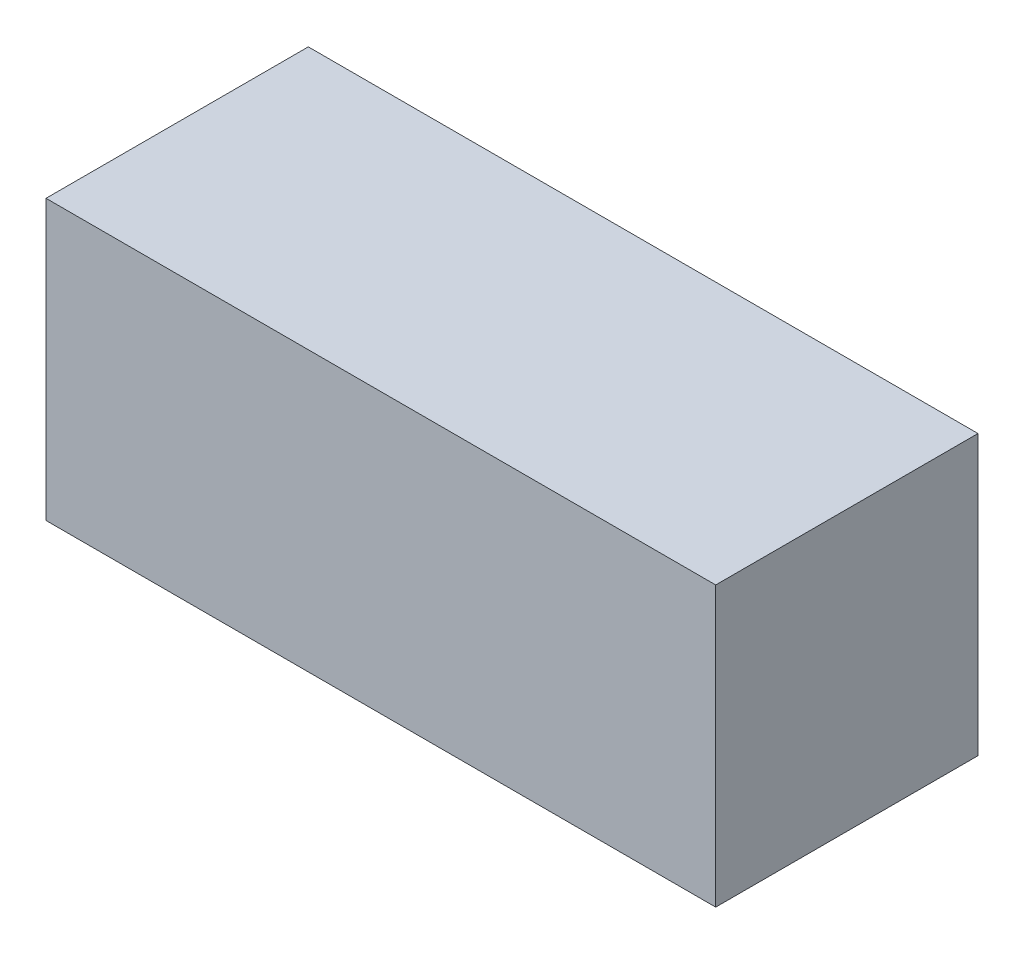
SolidWorks part; units mm, degrees
ref_plane "前视基准面" through (0, 0, 0) normal (0, 0, 1) x (1, 0, 0)
ref_plane "上视基准面" through (0, 0, 0) normal (0, 1, 0) x (1, 0, 0)
ref_plane "右视基准面" through (0, 0, 0) normal (1, 0, 0) x (0, 0, -1)
other "Configuration Table"
sketch "草图1" plane through (0, 0, 0) normal (0, 1, 0) x (1, 0, 0)
  line L1 (0, 0) -> (120, 0)
  line L2 (0, 0) -> (0, 47)
  line L3 (0, 47) -> (120, 47)
  line L4 (120, 0) -> (120, 47)
  dimension "D1" = 47
  dimension "D2" = 120
extrude "凸台-拉伸1" add sketch "草图1" along normal blind 50
